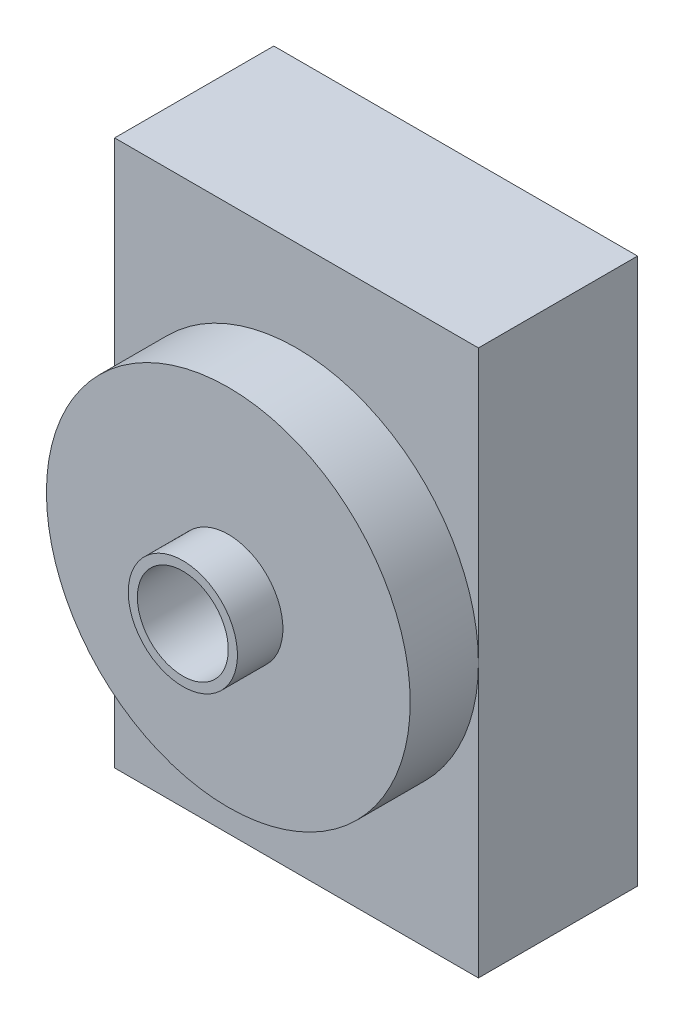
SolidWorks part; units mm, degrees
ref_plane "Front Plane" through (0, 0, 0) normal (0, 0, 1) x (1, 0, 0)
ref_plane "Top Plane" through (0, 0, 0) normal (0, 1, 0) x (1, 0, 0)
ref_plane "Right Plane" through (0, 0, 0) normal (1, 0, 0) x (0, 0, -1)
sketch "Sketch1" plane through (0, 0, 0) normal (0, 0, 1) x (1, 0, 0)
  circle A0 centre (0, 0) radius 25.4
  dimension "D1" = 50.8
extrude "Boss-Extrude1" add sketch "Sketch1" along normal blind 31.75
sketch "Sketch2" plane through (0, 0, 0) normal (0, 0, 1) x (1, 0, 0)
  circle A0 centre (0, 0) radius 7.62
  dimension "D1" = 15.24
extrude "Boss-Extrude2" add sketch "Sketch2" along normal blind 38.1
sketch "Sketch3" plane through (0, 0, 0) normal (0, 0, 1) x (1, 0, 0)
  line L1 (25.4, -38.1) -> (-25.4, -38.1)
  line L2 (25.4, -38.1) -> (25.4, 38.1)
  line L3 (25.4, 38.1) -> (-25.4, 38.1)
  line L4 (-25.4, -38.1) -> (-25.4, 38.1)
  line L5 (25.4, -38.1) -> (-25.4, 38.1) construction
  line L6 (25.4, 38.1) -> (-25.4, -38.1) construction
  point P0 (0, 0)
  dimension "D1" = 50.8
  dimension "D2" = 76.2
extrude "Boss-Extrude3" add sketch "Sketch3" along normal blind 22.225
sketch "Sketch4" plane through (0, 0, 0) normal (0, 0, 1) x (1, 0, 0)
  circle A0 centre (0, 0) radius 6.35
  dimension "D1" = 12.7
extrude "Cut-Extrude1" cut sketch "Sketch4" along normal through all
